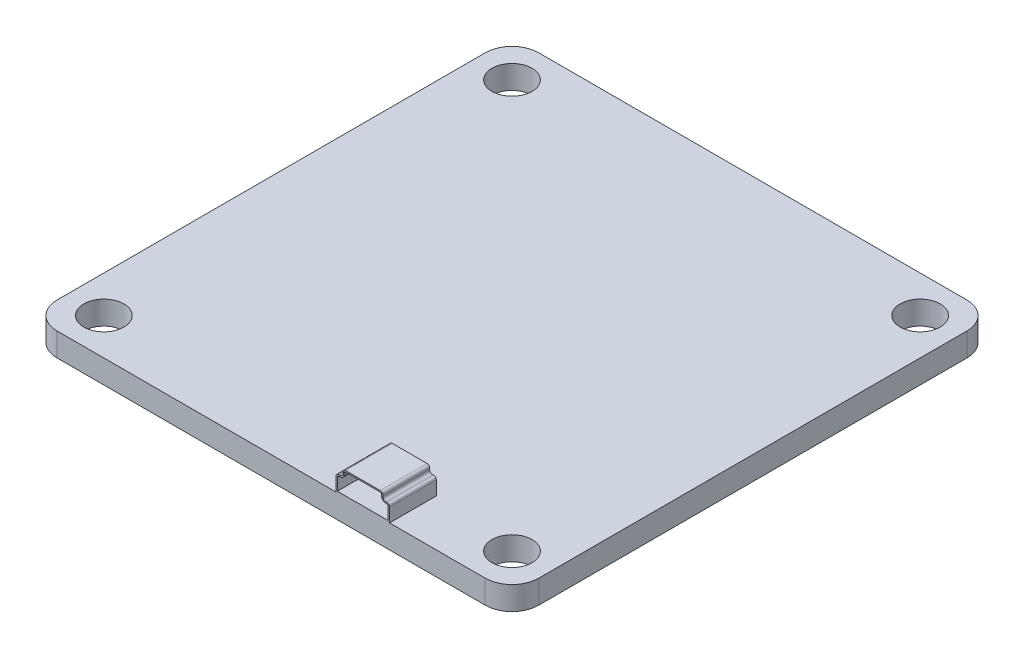
SolidWorks part; units mm, degrees
ref_plane "Front Plane" through (0, 0, 0) normal (0, 0, 1) x (1, 0, 0)
ref_plane "Top Plane" through (0, 0, 0) normal (0, 1, 0) x (1, 0, 0)
ref_plane "Right Plane" through (0, 0, 0) normal (1, 0, 0) x (0, 0, -1)
sketch "Sketch2" plane through (0, 0, 0) normal (0, 1, 0) x (1, 0, 0)
  line L1 (16, -18) -> (-16, -18)
  line L2 (18, -16) -> (18, 16)
  line L3 (16, 18) -> (-16, 18)
  line L4 (-18, -16) -> (-18, 16)
  line L5 (18, -18) -> (-18, 18) construction
  line L6 (18, 18) -> (-18, -18) construction
  line L7 (15.25, -15.25) -> (-15.25, -15.25) construction
  line L8 (15.25, -15.25) -> (15.25, 15.25) construction
  line L9 (15.25, 15.25) -> (-15.25, 15.25) construction
  line L10 (-15.25, -15.25) -> (-15.25, 15.25) construction
  line L11 (15.25, -15.25) -> (-15.25, 15.25) construction
  line L12 (15.25, 15.25) -> (-15.25, -15.25) construction
  circle A0 centre (-15.25, 15.25) radius 1.5
  circle A1 centre (15.25, 15.25) radius 1.5
  circle A2 centre (15.25, -15.25) radius 1.5
  circle A3 centre (-15.25, -15.25) radius 1.5
  arc A4 (-16, -18) -> (-18, -16) centre (-16, -16) cw
  arc A5 (16, -18) -> (18, -16) centre (16, -16) ccw
  arc A6 (18, 16) -> (16, 18) centre (16, 16) ccw
  arc A7 (-16, 18) -> (-18, 16) centre (-16, 16) ccw
  point P0 (0, 0)
  point P6 (0, 0)
  dimension "D4" = 3
  dimension "D5" = 2
  dimension "D1" = 36
  dimension "D2" = 36
  dimension "D3" = 30.5
extrude "Boss-Extrude1" add sketch "Sketch2" along normal blind 1.75
sketch "Sketch3" plane through (0, 0, 18) normal (0, 0, 1) x (1, 0, 0)
  line L0 (-16, 1.75) -> (16, 1.75) construction
  line L1 (5.5571, 3.5) -> (8.1507, 3.5)
  line L2 (4.8506, 2.7841) -> (4.8506, 1.75)
  line L3 (4.8506, 1.75) -> (8.8506, 1.75)
  line L4 (8.8506, 2.7841) -> (8.8506, 1.75)
  line L5 (5.5571, 3.4) -> (8.1507, 3.4)
  line L8 (5.0506, 2.9841) -> (5.1571, 2.9841)
  line L9 (5.3571, 3.3) -> (5.3571, 3.1841)
  line L12 (8.6506, 2.9841) -> (8.5507, 2.9841)
  line L13 (8.3507, 3.3) -> (8.3507, 3.1841)
  line L14 (8.2507, 3.3) -> (8.2507, 3.1841)
  line L15 (8.6506, 2.8841) -> (8.5507, 2.8841)
  line L16 (8.7506, 2.7841) -> (8.7506, 1.85)
  line L17 (4.9506, 1.85) -> (8.7506, 1.85)
  line L18 (4.9506, 2.7841) -> (4.9506, 1.85)
  line L19 (5.0506, 2.8841) -> (5.1571, 2.8841)
  line L20 (5.4571, 3.3) -> (5.4571, 3.1841)
  arc A0 (8.1507, 3.5) -> (8.3507, 3.3) centre (8.1507, 3.3) cw
  arc A1 (5.5571, 3.5) -> (5.3571, 3.3) centre (5.5571, 3.3) ccw
  arc A2 (8.8506, 2.7841) -> (8.6506, 2.9841) centre (8.6506, 2.7841) ccw
  arc A3 (8.5507, 2.9841) -> (8.3507, 3.1841) centre (8.5507, 3.1841) cw
  arc A4 (5.1571, 2.9841) -> (5.3571, 3.1841) centre (5.1571, 3.1841) ccw
  arc A5 (4.8506, 2.7841) -> (5.0506, 2.9841) centre (5.0506, 2.7841) cw
  arc A6 (8.1507, 3.4) -> (8.2507, 3.3) centre (8.1507, 3.3) cw
  arc A7 (8.5507, 2.8841) -> (8.2507, 3.1841) centre (8.5507, 3.1841) cw
  arc A8 (8.7506, 2.7841) -> (8.6506, 2.8841) centre (8.6506, 2.7841) ccw
  arc A9 (4.9506, 2.7841) -> (5.0506, 2.8841) centre (5.0506, 2.7841) cw
  arc A10 (5.1571, 2.8841) -> (5.4571, 3.1841) centre (5.1571, 3.1841) ccw
  arc A11 (5.5571, 3.4) -> (5.4571, 3.3) centre (5.5571, 3.3) ccw
  dimension "D1" = 0.2
  dimension "D2" = 0.1
extrude "Boss-Extrude2" add sketch "Sketch3" against normal blind 3
sketch "Sketch5" plane through (0, 0, 15) normal (0, 0, -1) x (-1, 0, 0)
  line L8 (-8.3507, 3.3) -> (-8.3507, 3.1841)
  line L9 (-8.5507, 2.9841) -> (-8.6506, 2.9841)
  line L10 (-8.8506, 2.7841) -> (-8.8506, 1.75)
  line L11 (-8.8506, 1.75) -> (-4.8506, 1.75)
  line L12 (-4.8506, 1.75) -> (-4.8506, 2.7841)
  line L13 (-5.0506, 2.9841) -> (-5.1571, 2.9841)
  line L14 (-5.3571, 3.1841) -> (-5.3571, 3.3)
  line L15 (-5.5571, 3.5) -> (-8.1507, 3.5)
  line L16 (-8.3507, 3.3) -> (-8.3507, 3.1841)
  line L17 (-8.5507, 2.9841) -> (-8.6506, 2.9841)
  line L18 (-8.8506, 2.7841) -> (-8.8506, 1.75)
  line L19 (-8.8506, 1.75) -> (-4.8506, 1.75)
  line L20 (-4.8506, 1.75) -> (-4.8506, 2.7841)
  line L21 (-5.0506, 2.9841) -> (-5.1571, 2.9841)
  line L22 (-5.3571, 3.1841) -> (-5.3571, 3.3)
  line L23 (-5.5571, 3.5) -> (-8.1507, 3.5)
  arc A6 (-8.1507, 3.5) -> (-8.3507, 3.3) centre (-8.1507, 3.3) ccw
  arc A7 (-8.5507, 2.9841) -> (-8.3507, 3.1841) centre (-8.5507, 3.1841) ccw
  arc A8 (-8.6506, 2.9841) -> (-8.8506, 2.7841) centre (-8.6506, 2.7841) ccw
  arc A9 (-4.8506, 2.7841) -> (-5.0506, 2.9841) centre (-5.0506, 2.7841) ccw
  arc A10 (-5.3571, 3.1841) -> (-5.1571, 2.9841) centre (-5.1571, 3.1841) ccw
  arc A11 (-5.3571, 3.3) -> (-5.5571, 3.5) centre (-5.5571, 3.3) ccw
  arc A12 (-8.1507, 3.5) -> (-8.3507, 3.3) centre (-8.1507, 3.3) ccw
  arc A13 (-8.5507, 2.9841) -> (-8.3507, 3.1841) centre (-8.5507, 3.1841) ccw
  arc A14 (-8.6506, 2.9841) -> (-8.8506, 2.7841) centre (-8.6506, 2.7841) ccw
  arc A15 (-4.8506, 2.7841) -> (-5.0506, 2.9841) centre (-5.0506, 2.7841) ccw
  arc A16 (-5.3571, 3.1841) -> (-5.1571, 2.9841) centre (-5.1571, 3.1841) ccw
  arc A17 (-5.3571, 3.3) -> (-5.5571, 3.5) centre (-5.5571, 3.3) ccw
  dimension "D1" = 0
extrude "Boss-Extrude3" add sketch "Sketch5" along normal blind 0.5
sketch "Sketch6" plane through (0, 0, 14.5) normal (0, 0, -1) x (-1, 0, 0)
  circle A0 centre (-7.6506, 2.2183) radius 0.25
  circle A1 centre (-6.8506, 2.2183) radius 0.25
  circle A2 centre (-6.0506, 2.2183) radius 0.25
  dimension "D1" = 0.5
  dimension "D2" = 0.8
  dimension "D3" = 0.8
extrude "Cut-Extrude1" cut sketch "Sketch6" against normal through all
